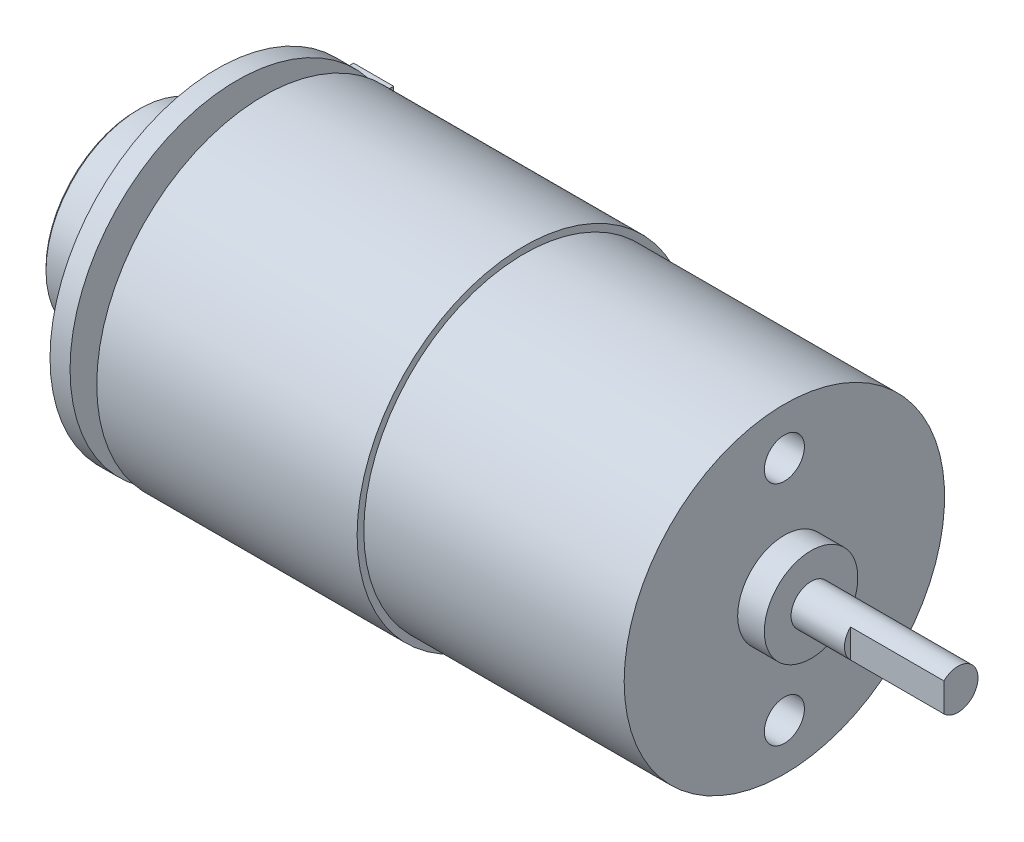
SolidWorks part; units mm, degrees
ref_plane "前视基准面" through (0, 0, 0) normal (0, 0, 1) x (1, 0, 0)
ref_plane "上视基准面" through (0, 0, 0) normal (0, 1, 0) x (1, 0, 0)
ref_plane "右视基准面" through (0, 0, 0) normal (1, 0, 0) x (0, 0, -1)
sketch "草图1" plane through (0, 0, 0) normal (0, 0, 1) x (1, 0, 0)
  line L0 (-61.9656, 0) -> (72.8167, 0) construction
  line L1 (0, 12) -> (0, 12.5)
  line L2 (0, 12.5) -> (-19.5, 12.5)
  line L3 (-19.5, 12.5) -> (-19.5, 0)
  line L4 (-19.5, 0) -> (19.5, 0)
  line L5 (19.5, 3.5) -> (19.5, 12)
  line L6 (19.5, 12) -> (0, 12)
  line L7 (19.5, 0) -> (32.5, 0)
  line L8 (32.5, 0) -> (32.5, 1.5)
  line L9 (32.5, 1.5) -> (21.5, 1.5)
  line L10 (21.5, 1.5) -> (21.5, 3.5)
  line L11 (21.5, 3.5) -> (19.5, 3.5)
revolve "旋转1" add sketch "草图1" angle 360 about L0
sketch "草图2" plane through (19.5, 0, 0) normal (1, 0, 0) x (0, 0, -1)
  line L0 (0, 0) -> (0, -8.5) construction
  line L1 (-7.0908, 0) -> (6.7968, 0) construction
  circle A0 centre (0, -8.5) radius 1.5
  circle A1 centre (0, 8.5) radius 1.5
extrude "切除-拉伸1" cut sketch "草图2" against normal blind 3
sketch "草图3" plane through (-19.5, 0, 0) normal (-1, 0, 0) x (0, 0, 1)
  line L0 (-14.4387, 0) -> (14.1815, 0) construction
  line L1 (0, 7.4214) -> (0, -8.3032) construction
  line L2 (-9.6547, 1.5) -> (-9.1547, 1.5)
  line L3 (-9.6547, 1.5) -> (-9.6547, -1.5)
  line L4 (-9.6547, -1.5) -> (-9.1547, -1.5)
  line L5 (-9.1547, 1.5) -> (-9.1547, -1.5)
  line L6 (-9.6547, 1.5) -> (-9.1547, -1.5) construction
  line L7 (-9.6547, -1.5) -> (-9.1547, 1.5) construction
  line L8 (9.6547, -1.5) -> (9.1547, -1.5)
  line L9 (9.6547, 1.5) -> (9.1547, 1.5)
  line L10 (9.1547, 1.5) -> (9.1547, -1.5)
  line L11 (9.6547, 1.5) -> (9.6547, -1.5)
  point P3 (-9.4047, 0)
extrude "凸台-拉伸1" add sketch "草图3" along normal blind 2
sketch "草图4" plane through (-21.5, 0, 0) normal (-1, 0, 0) x (0, 0, 1)
  circle A0 centre (0, 0) radius 12.5
extrude "凸台-拉伸2" add sketch "草图4" along normal blind 1.5
sketch "草图5" plane through (-23, 0, 0) normal (-1, 0, 0) x (0, 0, 1)
  circle A0 centre (0, 0) radius 0.5
extrude "凸台-拉伸3" add sketch "草图5" along normal blind 1
sketch "草图6" plane through (-24, 0, 0) normal (-1, 0, 0) x (0, 0, 1)
  circle A0 centre (0, 0) radius 7
extrude "凸台-拉伸4" add sketch "草图6" along normal blind 5
sketch "草图7" plane through (-23, 0, 0) normal (-1, 0, 0) x (0, 0, 1)
  line L0 (3.7312, 0) -> (-16.1288, 0) construction
  line L1 (-13.235, 4.7492) -> (-13.235, -4.7492)
  line L2 (-13.235, -4.7492) -> (-8.235, -4.7492)
  line L3 (-8.235, -4.7492) -> (-8.235, 4.7492)
  line L4 (-8.235, 4.7492) -> (-13.235, 4.7492)
  point P6 (-13.235, 0)
extrude "凸台-拉伸5" add sketch "草图7" along normal blind 3
chamfer "倒角1" distance 0.2 angle 45 1 edges at (-29, 0, 7)
sketch "草图8" plane through (0, 0, 0) normal (0, 1, 0) x (1, 0, 0)
  line L0 (32.5, -1.5) -> (25.5, -1.5)
  line L1 (21.5, -1.5) -> (32.5, -1.5) construction
  line L2 (25.5, -1.5) -> (25.5, -1.05)
  line L3 (25.5, -1.05) -> (32.5, -1.05)
  line L4 (32.5, -1.5) -> (32.5, 1.5) construction
  line L5 (32.5, -1.05) -> (32.5, -1.5)
extrude "切除-拉伸2" cut sketch "草图8" against normal through all both and the other way through all
